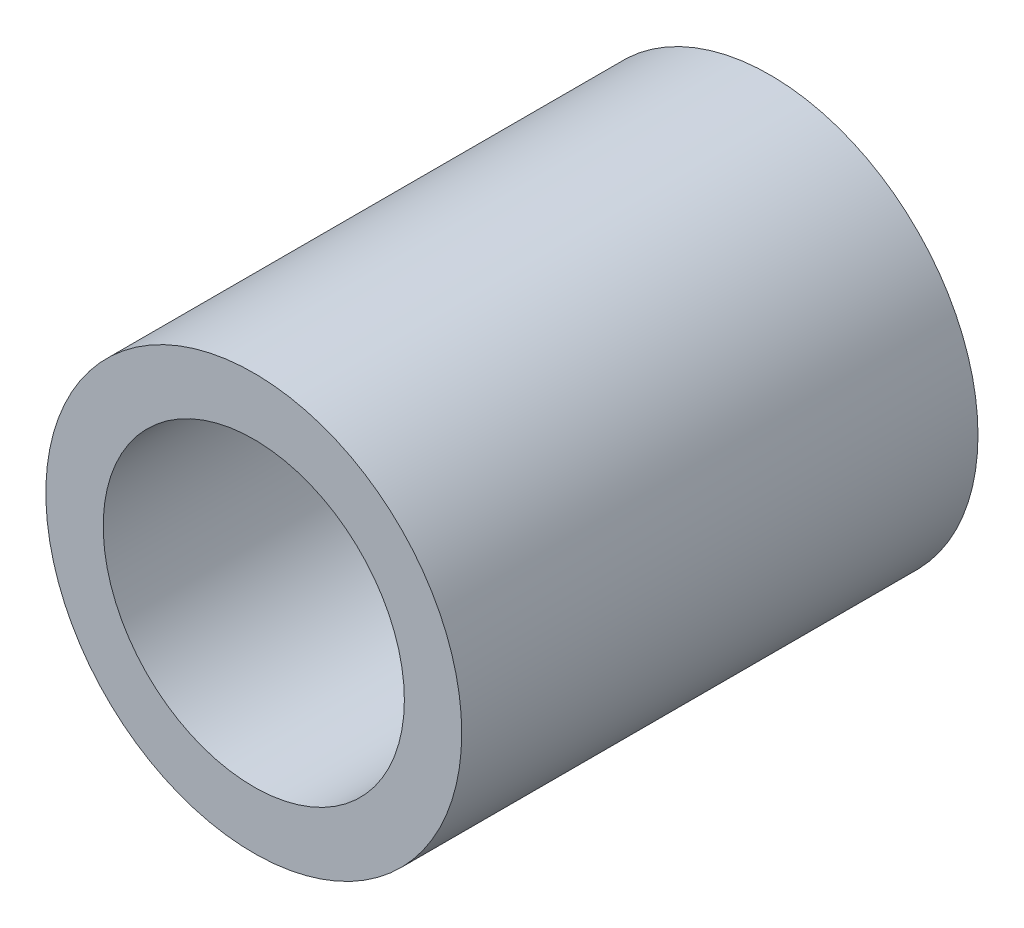
SolidWorks part; units mm, degrees
material "3.1325 (EN-AW 2017A)"
ref_plane "Płaszczyzna przednia" through (0, 0, 0) normal (0, 0, 1) x (1, 0, 0)
ref_plane "Płaszczyzna górna" through (0, 0, 0) normal (0, 1, 0) x (1, 0, 0)
ref_plane "Płaszczyzna prawa" through (0, 0, 0) normal (1, 0, 0) x (0, 0, -1)
sketch "Szkic1" plane through (0, 0, 0) normal (0, 0, 1) x (1, 0, 0)
  circle A0 centre (-4.4356, 1.8048) radius 7.25
  circle A1 centre (-4.4356, 1.8048) radius 5.25
  dimension "D1" = 2
  dimension "D2" = 10.5
extrude "Dodanie-wyciągnięcie1" add sketch "Szkic1" along normal blind 18
